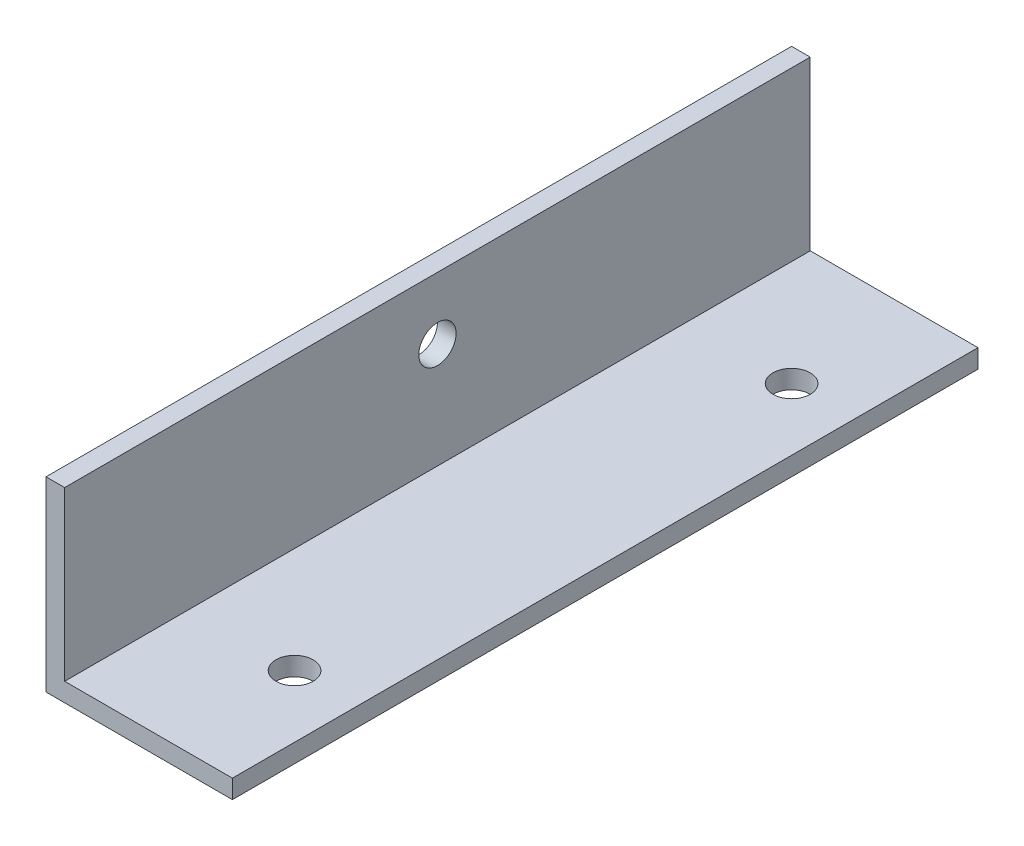
SolidWorks part; units mm, degrees
ref_plane "Plan de face" through (0, 0, 0) normal (0, 0, 1) x (1, 0, 0)
ref_plane "Plan de dessus" through (0, 0, 0) normal (0, 1, 0) x (1, 0, 0)
ref_plane "Plan de droite" through (0, 0, 0) normal (1, 0, 0) x (0, 0, -1)
sketch "Esquisse1" plane through (0, 0, 0) normal (0, 0, 1) x (1, 0, 0)
  line L1 (0, 0) -> (1.5, 0)
  line L2 (0, 0) -> (0, 15)
  line L3 (0, 15) -> (1.5, 15)
  line L4 (1.5, 1.5) -> (1.5, 15)
  line L5 (1.5, 0) -> (15, 0)
  line L7 (1.5, 1.5) -> (15, 1.5)
  line L8 (15, 0) -> (15, 1.5)
  dimension "D1" = 1.5
  dimension "D2" = 1.5
  dimension "D3" = 15
  dimension "D4" = 13.5
  dimension "D5" = 13.5
extrude "Extrusion1" add sketch "Esquisse1" along normal blind 60
sketch "Esquisse2" plane through (0, 0, 0) normal (-1, 0, 0) x (0, 0, 1)
  line L0 (60, 15) -> (0, 15) construction
  line L1 (0, 15) -> (0, 0) construction
  circle A0 centre (30, 10) radius 1.5
  dimension "D2" = 3
  dimension "D1" = 5
  dimension "D3" = 30
extrude "Extrusion2" cut sketch "Esquisse2" against normal blind 60
sketch "Esquisse3" plane through (0, 0, 0) normal (0, -1, 0) x (1, 0, 0)
  line L0 (15, 60) -> (15, 0) construction
  line L1 (0, 0) -> (15, 0) construction
  circle A0 centre (10, 10) radius 1.5
  dimension "D1" = 3
  dimension "D2" = 5
  dimension "D3" = 10
extrude "Extrusion3" cut sketch "Esquisse3" against normal blind 60
pattern_linear "Répétition linéaire1" count 2 spacing 40 along (0, 0, 1) of "Extrusion3"
